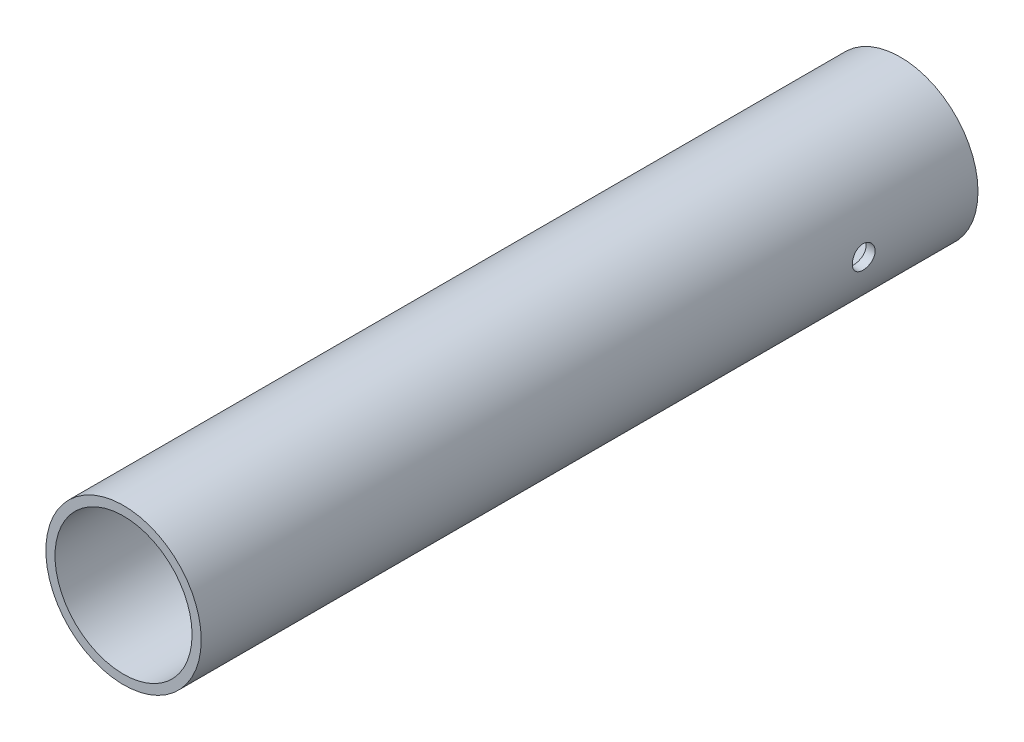
SolidWorks part; units mm, degrees
ref_plane "Front Plane" through (0, 0, 0) normal (0, 0, 1) x (1, 0, 0)
ref_plane "Top Plane" through (0, 0, 0) normal (0, 1, 0) x (1, 0, 0)
ref_plane "Right Plane" through (0, 0, 0) normal (1, 0, 0) x (0, 0, -1)
sketch "Sketch1" plane through (0, 0, 0) normal (0, 0, 1) x (1, 0, 0)
  circle A0 centre (0, 0) radius 15
  circle A1 centre (0, 0) radius 17
  dimension "D1" = 30
  dimension "D2" = 2
extrude "Boss-Extrude1" add sketch "Sketch1" along normal mid plane 170 contours A1 A0
sketch "Sketch2" plane through (0, 0, 0) normal (1, 0, 0) x (0, 0, -1)
  line L0 (0, 0) -> (60, 0) construction
  circle A0 centre (60, 0) radius 2.5
  dimension "D1" = 5
  dimension "D2" = 60
extrude "Cut-Extrude1" cut sketch "Sketch2" against normal through all both and the other way through all
